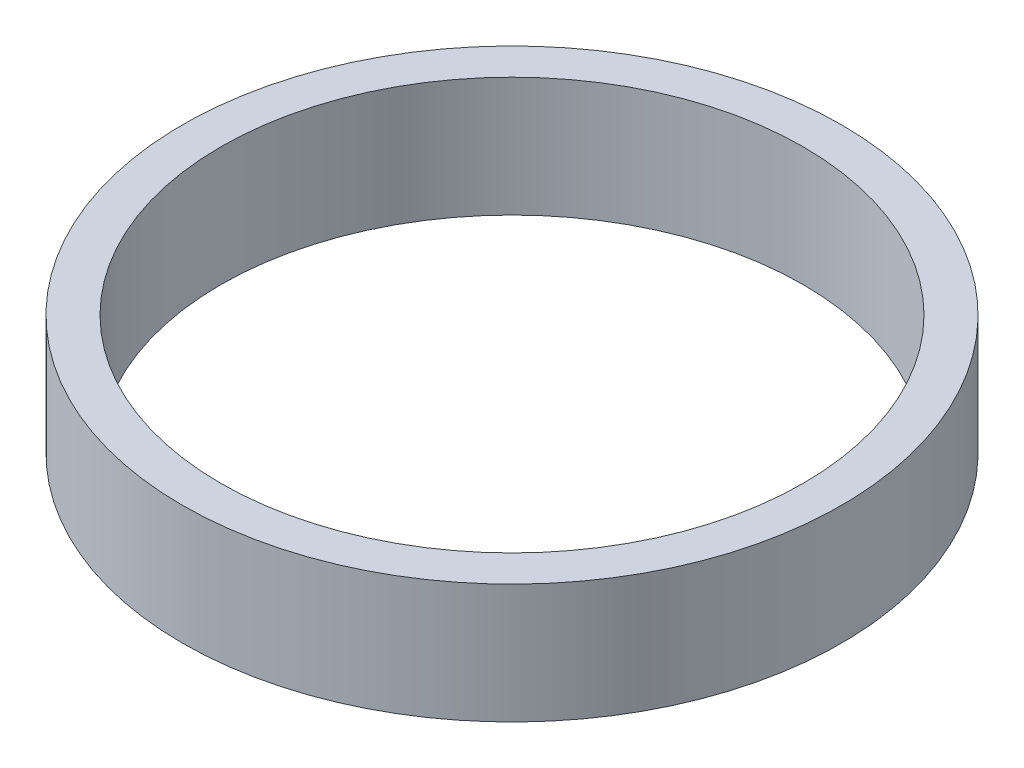
SolidWorks part; units mm, degrees
ref_plane "Front Plane" through (0, 0, 0) normal (0, 0, 1) x (1, 0, 0)
ref_plane "Top Plane" through (0, 0, 0) normal (0, 1, 0) x (1, 0, 0)
ref_plane "Right Plane" through (0, 0, 0) normal (1, 0, 0) x (0, 0, -1)
sketch "Sketch1" plane through (0, 0, 0) normal (0, 1, 0) x (1, 0, 0)
  circle A0 centre (0, 0) radius 30.5
  circle A1 centre (0, 0) radius 34.5
  dimension "D1" = 61
  dimension "D2" = 69
extrude "Boss-Extrude1" add sketch "Sketch1" along normal blind 12.5
